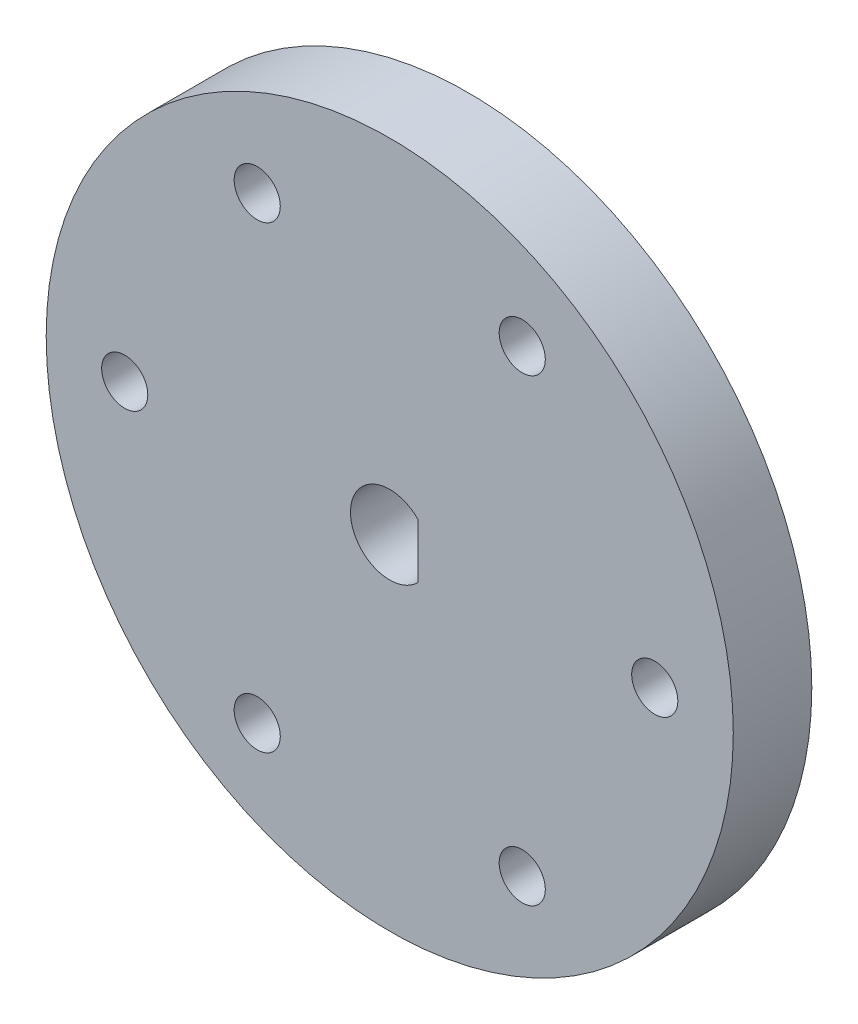
SolidWorks part; units mm, degrees
ref_plane "Alzado" through (0, 0, 0) normal (0, 0, 1) x (1, 0, 0)
ref_plane "Planta" through (0, 0, 0) normal (0, 1, 0) x (1, 0, 0)
ref_plane "Vista lateral" through (0, 0, 0) normal (1, 0, 0) x (0, 0, -1)
sketch "Croquis1" plane through (0, 0, 0) normal (0, 0, 1) x (1, 0, 0)
  line L0 (2.9047, 2.75) -> (2.9047, -2.75)
  circle A0 centre (0, 0) radius 35
  arc A1 (2.9047, 2.75) -> (2.9047, -2.75) centre (0, 0) ccw
  dimension "D1" = 70
  dimension "D2" = 8
  dimension "D3" = 5.5
extrude "Saliente-Extruir1" add sketch "Croquis1" along normal blind 8
sketch "Croquis2" plane through (0, 0, 8) normal (0, 0, 1) x (1, 0, 0)
  line L0 (0, 0) -> (0, 35) construction
  line L1 (0, 0) -> (35, 0) construction
  circle A0 centre (0, 0) radius 35 construction
  circle A1 centre (27, 0) radius 2.35
  circle A2 centre (13.5, -23.3827) radius 2.35
  circle A3 centre (-13.5, -23.3827) radius 2.35
  circle A4 centre (-27, 0) radius 2.35
  circle A5 centre (-13.5, 23.3827) radius 2.35
  circle A6 centre (13.5, 23.3827) radius 2.35
  point P22 (0, 0)
  dimension "D2" = 4.7
  dimension "D1" = 8
  dimension "D3" = 6
extrude "Cortar-Extruir1" cut sketch "Croquis2" against normal blind 5
